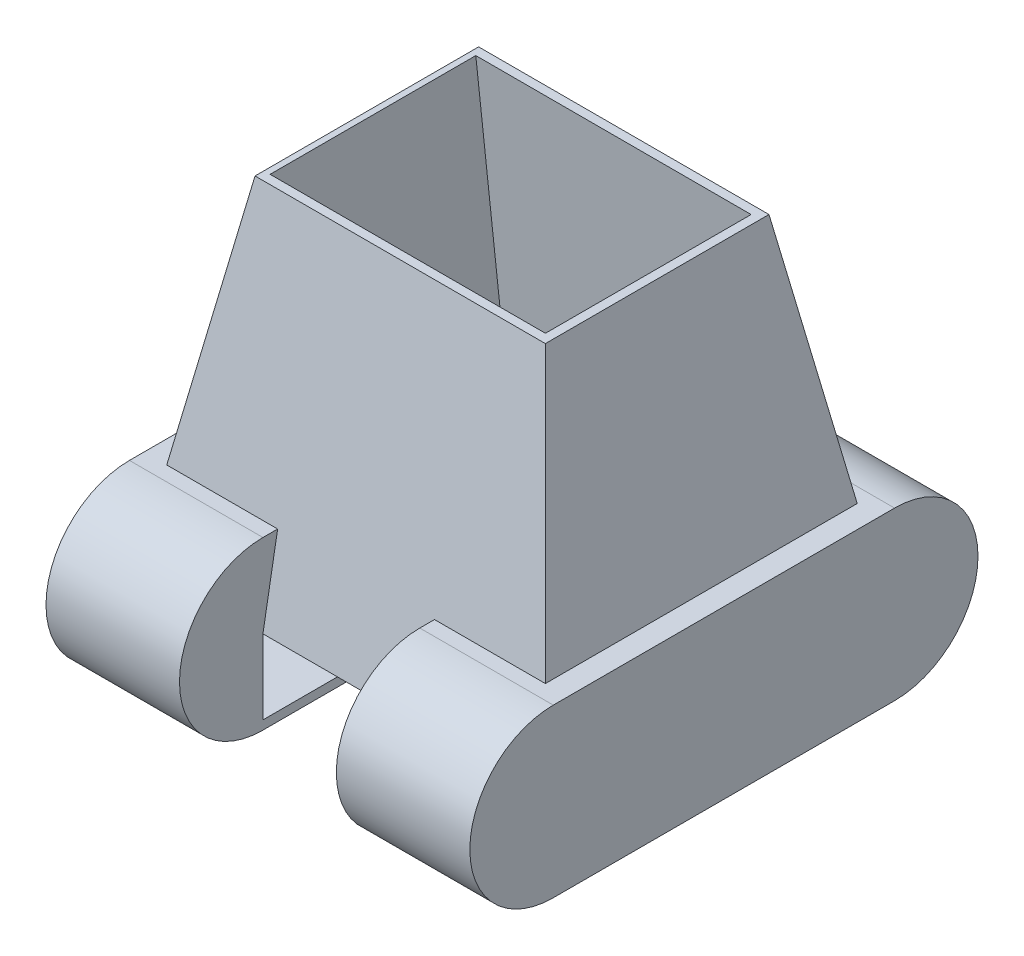
SolidWorks part; units mm, degrees
ref_plane "Front Plane" through (0, 0, 0) normal (0, 0, 1) x (1, 0, 0)
ref_plane "Top Plane" through (0, 0, 0) normal (0, 1, 0) x (1, 0, 0)
ref_plane "Right Plane" through (0, 0, 0) normal (1, 0, 0) x (0, 0, -1)
sketch "Sketch1" plane through (0, 0, 0) normal (0, 1, 0) x (1, 0, 0)
  line L1 (0, 0) -> (52.2, 0)
  line L2 (0, 0) -> (0, -40.2)
  line L3 (0, -40.2) -> (52.2, -40.2)
  line L4 (52.2, 0) -> (52.2, -40.2)
  dimension "D1" = 52.2
  dimension "D2" = 40.2
extrude "Boss-Extrude1" add sketch "Sketch1" against normal blind 60 draft 10 draft outward yes
sketch "Sketch5" plane through (0, 0, 0) normal (1, 0, 0) x (0, 0, -1)
  line L0 (4.0832, -54.1555) -> (-32.4951, -58)
  line L1 (4.0832, -54.1555) -> (-5.2524, 34.6661)
  line L2 (-32.4951, -58) -> (-41.8307, 30.8215)
  line L3 (-5.2524, 34.6661) -> (-41.8307, 30.8215)
  line L7 (10.5796, -60) -> (-50.7796, -60) construction
  dimension "D1" = 2
  dimension "D2" = 6
  dimension "D3" = 1.6
  dimension "D4" = 88.8215
  dimension "D5" = 1.6
extrude "Cut-Extrude2" cut sketch "Sketch5" along normal blind 49.5 from offset 1.1
sketch "Sketch18" plane through (0, -53.9882, -5.6744) normal (0, 0.9945, 0.1045) x (1, 0, 0)
  line L0 (1.1, -1.6) -> (50.6, -38.3798)
  line L1 (1.1, -38.3798) -> (50.6, -1.6)
  circle A0 centre (25.85, -19.9899) radius 7.5
  dimension "D1" = 15
extrude "Cut-Extrude3" cut sketch "Sketch18" against normal through all contours A0
sketch "Sketch19" plane through (0, 0, 0) normal (1, 0, 0) x (0, 0, -1)
  line L0 (10.5796, -60) -> (-50.7796, -60) construction
  line L1 (10.5796, -75) -> (-50.7796, -75)
  line L2 (10.5796, -45) -> (-50.7796, -45)
  line L3 (10.5796, -60) -> (-50.7796, -60) construction
  arc A0 (10.5796, -75) -> (10.5796, -45) centre (10.5796, -60) ccw
  arc A1 (-50.7796, -45) -> (-50.7796, -75) centre (-50.7796, -60) ccw
  point P2 (-20.1, -60)
  dimension "D1" = 15
  dimension "D2" = 61.3592
sketch "Sketch21" plane through (0, 0, 0) normal (1, 0, 0) x (0, 0, -1)
  line L0 (10.5796, -60) -> (-50.7796, -60) construction
  line L1 (10.5796, -75) -> (-50.7796, -75)
  line L2 (10.5796, -45) -> (-50.7796, -45)
  arc A0 (10.5796, -75) -> (10.5796, -45) centre (10.5796, -60) ccw
  arc A1 (-50.7796, -45) -> (-50.7796, -75) centre (-50.7796, -60) ccw
  point P4 (-20.1, -60)
  dimension "D1" = 15
extrude "Boss-Extrude15" add sketch "Sketch19" against normal blind 12 and the other way blind 12
extrude "Boss-Extrude16" add sketch "Sketch21" along normal blind 12 and the other way blind 12 from offset 52.2
sketch "Sketch22" plane through (40.2, 0, 0) normal (-1, 0, 0) x (0, 0, 1)
  line L0 (50.7796, -75) -> (-10.5796, -75) construction
  line L1 (-10.5796, -60) -> (50.7796, -60)
  line L2 (-10.5796, -60) -> (-10.5796, -73.4)
  line L3 (-10.5796, -73.4) -> (50.7796, -73.4)
  line L4 (50.7796, -60) -> (50.7796, -73.4)
  dimension "D1" = 1.6
extrude "Cut-Extrude4" cut sketch "Sketch22" against normal blind 22.2
sketch "Sketch23" plane through (12, 0, 0) normal (1, 0, 0) x (0, 0, -1)
  line L0 (-50.7796, -75) -> (10.5796, -75) construction
  line L1 (10.5796, -60) -> (-50.7796, -60)
  line L2 (10.5796, -60) -> (10.5796, -73.4)
  line L3 (10.5796, -73.4) -> (-50.7796, -73.4)
  line L4 (-50.7796, -60) -> (-50.7796, -73.4)
  dimension "D1" = 1.6
extrude "Cut-Extrude5" cut sketch "Sketch23" against normal blind 22.2
sketch "Sketch24" plane through (40.2, 0, 0) normal (-1, 0, 0) x (0, 0, 1)
sketch "Sketch25" plane through (12, 0, 0) normal (1, 0, 0) x (0, 0, -1)
  line L0 (3.1209, -45) -> (4.0832, -54.1555)
  line L1 (4.0832, -54.1555) -> (3.1209, -45) construction
  line L2 (4.0832, -54.1555) -> (-32.4951, -58)
  line L3 (-32.4951, -58) -> (-33.8615, -45)
  line L4 (-33.8615, -45) -> (3.1209, -45)
extrude "Cut-Extrude6" cut sketch "Sketch25" against normal blind 10.9
sketch "Sketch27" plane through (40.2, 0, 0) normal (-1, 0, 0) x (0, 0, 1)
  line L0 (-3.1209, -45) -> (-4.0832, -54.1555)
  line L1 (-4.0832, -54.1555) -> (32.4951, -58)
  line L2 (32.4951, -58) -> (33.8615, -45)
  line L3 (33.8615, -45) -> (-3.1209, -45)
extrude "Cut-Extrude7" cut sketch "Sketch27" against normal blind 10.4
sketch "Sketch28" plane through (0, 0, 0) normal (0, 0.1736, -0.9848) x (-1, 0, 0)
  text T0 "GUIMO" font "Tw Cen MT Condensed" height in points 60
extrude "Boss-Extrude17" add sketch "Sketch28" along normal blind 1
sketch "Sketch29" plane through (0, -53.9882, -5.6744) normal (0, 0.9945, 0.1045) x (1, 0, 0)
  line L0 (50.6, -38.3798) -> (1.1, -38.3798) construction
  line L1 (50.6, -1.6) -> (1.1, -1.6) construction
  line L2 (1.1, -38.3798) -> (1.1, -1.6) construction
  circle A0 centre (9.1, -9.6) radius 5.3
  dimension "D1" = 10.6
  dimension "D2" = 36.7798
  dimension "D3" = 8
  dimension "D4" = 8
extrude "Cut-Extrude8" cut sketch "Sketch29" against normal blind 4
